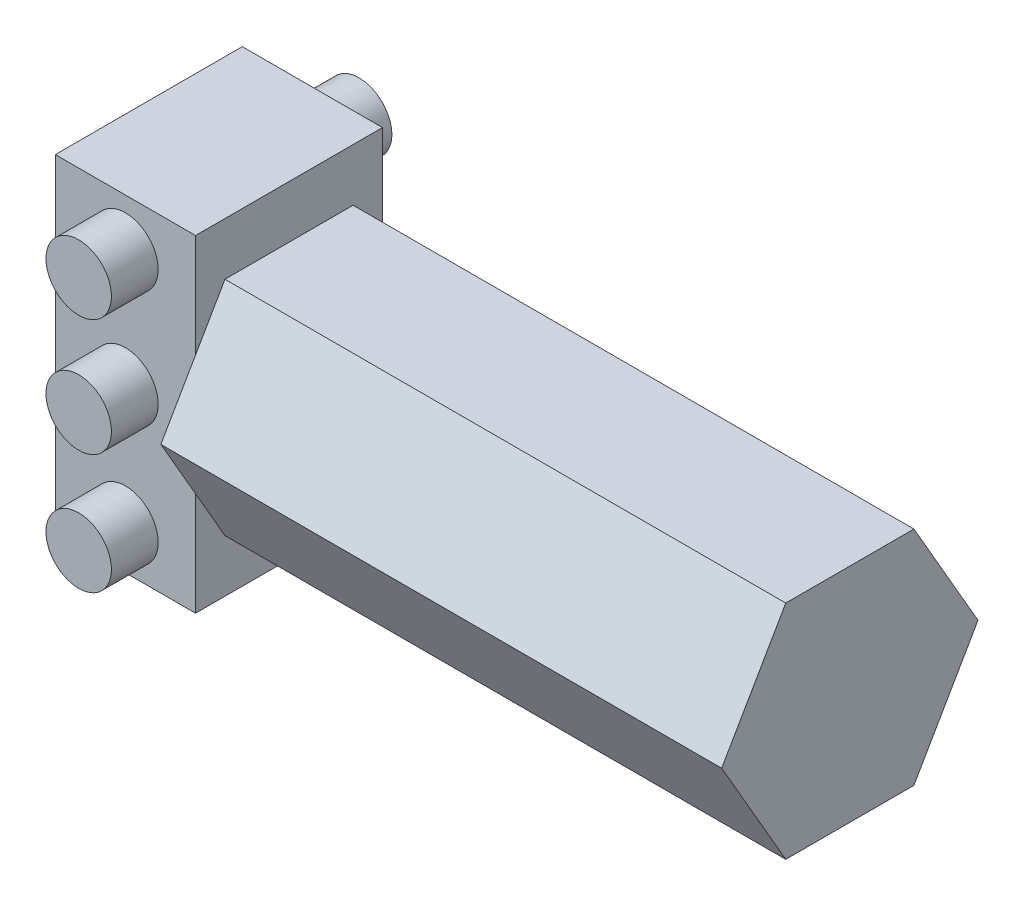
SolidWorks part; units mm, degrees
ref_plane "Front Plane" through (0, 0, 0) normal (0, 0, 1) x (1, 0, 0)
ref_plane "Top Plane" through (0, 0, 0) normal (0, 1, 0) x (1, 0, 0)
ref_plane "Right Plane" through (0, 0, 0) normal (1, 0, 0) x (0, 0, -1)
sketch "Sketch2" plane through (0, 0, 0) normal (0, 0, 1) x (1, 0, 0)
  line L1 (0, 0) -> (7.62, 0)
  line L2 (0, 0) -> (0, 17.78)
  line L3 (0, 17.78) -> (7.62, 17.78)
  line L4 (7.62, 0) -> (7.62, 17.78)
  dimension "D1" = 17.78
  dimension "D2" = 7.62
extrude "Boss-Extrude1" add sketch "Sketch2" along normal blind 10.16
sketch "Sketch3" plane through (7.62, 0, 0) normal (1, 0, 0) x (0, 0, -1)
  line L0 (0, 0) -> (0, 17.78) construction
  line L1 (1.8857, 8.89) -> (-1.5972, 14.9225)
  line L2 (-1.5972, 14.9225) -> (-8.5628, 14.9225)
  line L3 (-8.5628, 14.9225) -> (-12.0457, 8.89)
  line L4 (-12.0457, 8.89) -> (-8.5628, 2.8575)
  line L5 (-8.5628, 2.8575) -> (-1.5972, 2.8575)
  line L6 (-1.5972, 2.8575) -> (1.8857, 8.89)
  line L10 (-10.16, 0) -> (0, 0) construction
  circle A0 centre (-5.08, 8.89) radius 6.0325 construction
  point P15 (0, 8.89)
  point P16 (-5.08, 0)
  dimension "D1" = 6.9657
extrude "Boss-Extrude3" add sketch "Sketch3" along normal blind 30.48
sketch "Sketch6" plane through (0, 0, 10.16) normal (0, 0, 1) x (1, 0, 0)
  line L0 (7.62, 17.78) -> (0, 17.78) construction
  circle A0 centre (3.81, 15.1671) radius 1.778
  circle A1 centre (3.81, 8.8171) radius 1.778
  circle A2 centre (3.81, 2.3139) radius 1.778
  point P12 (3.81, 17.78)
  dimension "D1" = 6.35
  dimension "D2" = 3.556
  dimension "D3" = 3.556
  dimension "D4" = 3.556
sketch "Sketch8" plane through (0, 0, 0) normal (0, 0, -1) x (-1, 0, 0)
  line L0 (0, 0) -> (-7.62, 0) construction
  circle A0 centre (-3.81, 15.1671) radius 1.778
  circle A1 centre (-3.81, 8.8171) radius 1.778
  circle A2 centre (-3.81, 2.3139) radius 1.7214
  point P13 (-3.81, 0)
  dimension "D1" = 6.35
  dimension "D2" = 3.556
  dimension "D3" = 3.556
  dimension "D4" = 3.4427
extrude "Boss-Extrude4" add sketch "Sketch8" along normal blind 2.54
extrude "Boss-Extrude5" add sketch "Sketch6" along normal blind 2.54
